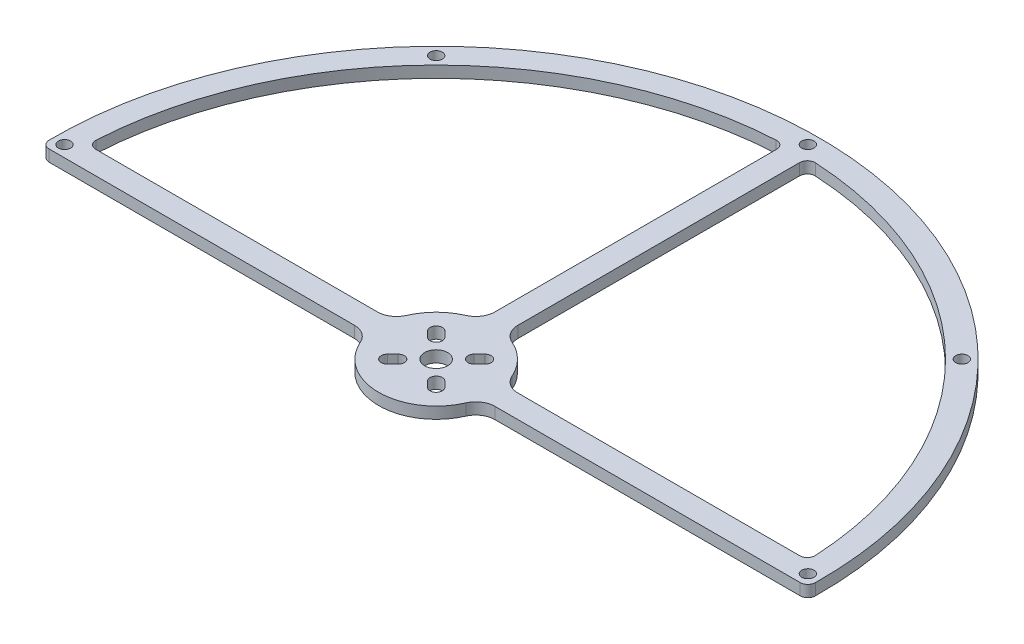
SolidWorks part; units mm, degrees
ref_plane "前视基准面" through (0, 0, 0) normal (0, 0, 1) x (1, 0, 0)
ref_plane "上视基准面" through (0, 0, 0) normal (0, 1, 0) x (1, 0, 0)
ref_plane "右视基准面" through (0, 0, 0) normal (1, 0, 0) x (0, 0, -1)
other "Configuration Table"
sketch "草图1" plane through (0, 0, 0) normal (0, 1, 0) x (1, 0, 0)
  line L1 (4.9497, -4.9497) -> (6.364, -6.364) construction
  line L4 (6.0811, -3.8184) -> (7.4953, -5.2326)
  line L5 (3.8184, -6.0811) -> (5.2326, -7.4953)
  line L9 (-4.9497, -4.9497) -> (-6.364, -6.364) construction
  line L10 (-3.8184, -6.0811) -> (-5.2326, -7.4953)
  line L11 (-6.0811, -3.8184) -> (-7.4953, -5.2326)
  line L15 (-4.9497, 4.9497) -> (-6.364, 6.364) construction
  line L16 (-6.0811, 3.8184) -> (-7.4953, 5.2326)
  line L17 (-3.8184, 6.0811) -> (-5.2326, 7.4953)
  line L21 (4.9497, 4.9497) -> (6.364, 6.364) construction
  line L22 (3.8184, 6.0811) -> (5.2326, 7.4953)
  line L23 (6.0811, 3.8184) -> (7.4953, 5.2326)
  line L26 (-97.8949, -3) -> (-18.3303, -3)
  line L36 (-7.2627, -5) -> (7.2627, -5) construction
  line L38 (-7.2627, 5) -> (7.2627, 5) construction
  line L40 (-5, 7.2627) -> (-5, -7.2627) construction
  line L41 (5, 7.2627) -> (5, -7.2627) construction
  line L43 (-3, -0.0867) -> (-3, 0.0867)
  line L44 (-99.8583, 2.8856) -> (99.8583, -2.8856) construction
  line L47 (-99.8583, -2.8856) -> (99.8583, 2.8856) construction
  line L52 (0, 0) -> (2.9398, 99.8567) construction
  line L53 (-2.9398, 99.8567) -> (0, 0) construction
  line L54 (-0.0883, 3) -> (0.0883, 3)
  line L56 (-91.7639, 3) -> (-18.3303, 3)
  line L57 (3, -0.0867) -> (3, 0.0867)
  line L58 (-3, 18.3303) -> (-3, 91.7639)
  line L59 (3, 18.3303) -> (3, 91.7639)
  line L61 (18.3303, 3) -> (91.7639, 3)
  line L63 (18.3303, -3) -> (97.8949, -3)
  circle A9 centre (0, 0) radius 8 construction
  arc A12 (6.0811, -3.8184) -> (3.8184, -6.0811) centre (4.9497, -4.9497) ccw
  arc A13 (5.2326, -7.4953) -> (7.4953, -5.2326) centre (6.364, -6.364) ccw
  arc A16 (-3.8184, -6.0811) -> (-6.0811, -3.8184) centre (-4.9497, -4.9497) ccw
  arc A17 (-7.4953, -5.2326) -> (-5.2326, -7.4953) centre (-6.364, -6.364) ccw
  arc A20 (-6.0811, 3.8184) -> (-3.8184, 6.0811) centre (-4.9497, 4.9497) ccw
  arc A21 (-5.2326, 7.4953) -> (-7.4953, 5.2326) centre (-6.364, 6.364) ccw
  arc A24 (3.8184, 6.0811) -> (6.0811, 3.8184) centre (4.9497, 4.9497) ccw
  arc A25 (7.4953, 5.2326) -> (5.2326, 7.4953) centre (6.364, 6.364) ccw
  arc A28 (-5.1088, 93.7609) -> (-93.7609, 5.1088) centre (0, 0) ccw
  circle A30 centre (0, 0) radius 64.77 construction
  arc A34 (-6, 13.7477) -> (-13.7477, 6) centre (0, 0) ccw
  circle A36 centre (0, 0) radius 88.9 construction
  arc A61 (96.8535, -3) -> (-96.8535, -3) centre (0, 0) ccw construction
  circle A62 centre (0, 96.9) radius 1.6
  circle A63 centre (68.5186, 68.5186) radius 1.6
  circle A64 centre (96.9, 0) radius 1.6
  circle A68 centre (-96.9, 0) radius 1.6
  circle A69 centre (-68.5186, 68.5186) radius 1.6
  circle A70 centre (68.5186, -68.5186) radius 1.6 [skipped]
  circle A71 centre (0, -96.9) radius 1.6 [skipped]
  circle A72 centre (-68.5186, -68.5186) radius 1.6 [skipped]
  circle A74 centre (0, 0) radius 3
  arc A75 (13.7477, 6) -> (6, 13.7477) centre (0, 0) ccw
  arc A76 (99.8948, -1.0204) -> (-99.8948, -1.0204) centre (0, 0) ccw
  arc A78 (-13.7477, -6) -> (13.7477, -6) centre (0, 0) ccw
  arc A79 (93.7609, 5.1088) -> (5.1088, 93.7609) centre (0, 0) ccw
  arc A80 (-97.8949, -3) -> (-99.8948, -1.0204) centre (-97.8949, -1) cw
  arc A81 (97.8949, -3) -> (99.8948, -1.0204) centre (97.8949, -1) ccw
  arc A82 (3, 91.7639) -> (5.1088, 93.7609) centre (5, 91.7639) cw
  arc A83 (-3, 91.7639) -> (-5.1088, 93.7609) centre (-5, 91.7639) ccw
  arc A84 (91.7639, 3) -> (93.7609, 5.1088) centre (91.7639, 5) ccw
  arc A85 (-91.7639, 3) -> (-93.7609, 5.1088) centre (-91.7639, 5) cw
  arc A86 (-13.7477, -6) -> (-18.3303, -3) centre (-18.3303, -8) ccw
  arc A87 (18.3303, -3) -> (13.7477, -6) centre (18.3303, -8) ccw
  arc A88 (18.3303, 3) -> (13.7477, 6) centre (18.3303, 8) cw
  arc A89 (6, 13.7477) -> (3, 18.3303) centre (8, 18.3303) cw
  arc A90 (-13.7477, 6) -> (-18.3303, 3) centre (-18.3303, 8) cw
  arc A91 (-6, 13.7477) -> (-3, 18.3303) centre (-8, 18.3303) ccw
  point P22 (5.6569, -5.6569)
  point P28 (0, 0)
  point P36 (-5.6569, -5.6569)
  point P50 (-5.6569, 5.6569)
  point P64 (5.6569, 5.6569)
  point P69 (0, 0)
  point P90 (14.6969, 3)
  point P93 (3, 14.6969)
  point P97 (-5, 91.7639)
  point P131 (-59.3933, 76.564)
  point P151 (0, 0)
  dimension "D2" = 30
  dimension "D3" = 2
  dimension "D4" = 6
  dimension "D5" = 199.8
  dimension "D6" = 5
  dimension "D7" = 16
  dimension "D9" = 3.2
  dimension "D11" = 8
extrude "凸台-拉伸1" add sketch "草图1" along normal blind 3
